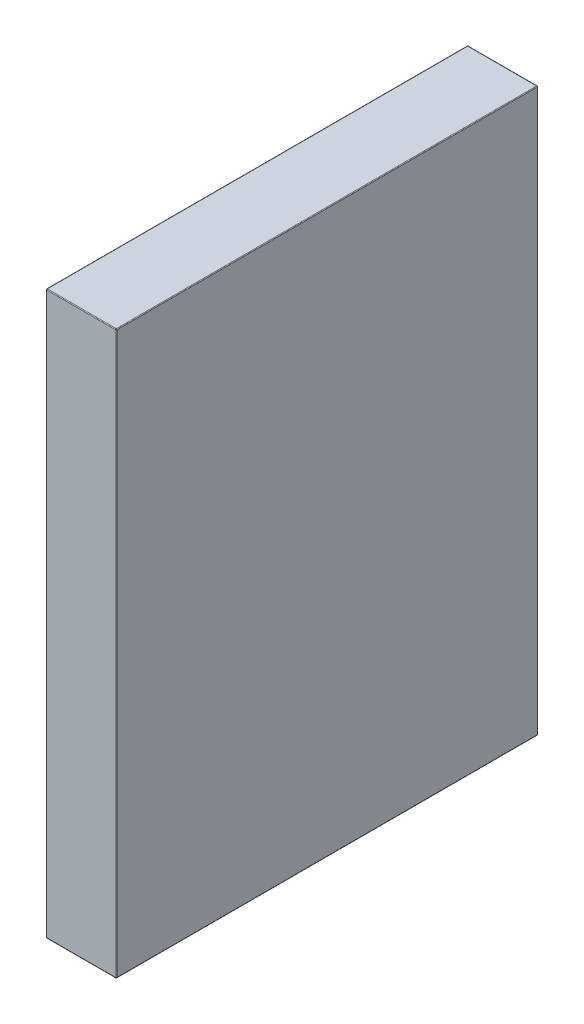
SolidWorks part; units mm, degrees
ref_plane "Front Plane" through (0, 0, 0) normal (1, 0, 0) x (0, 1, 0)
ref_plane "Top Plane" through (0, 0, 0) normal (0, 0, 1) x (0, 1, 0)
ref_plane "Right Plane" through (0, 0, 0) normal (0, 1, 0) x (-1, 0, 0)
sketch "Sketch1" plane through (0, 0, 0) normal (0, 0, 1) x (0, 1, 0)
  line L1 (-40, -5) -> (40, -5)
  line L2 (-40, -5) -> (-40, 5)
  line L3 (-40, 5) -> (40, 5)
  line L4 (40, -5) -> (40, 5)
  line L5 (-40, -5) -> (40, 5) construction
  line L6 (-40, 5) -> (40, -5) construction
  point P0 (0, 0)
  dimension "D1" = 80
  dimension "D2" = 10
extrude "Boss-Extrude1" add sketch "Sketch1" along normal blind 60
fillet "Fillet1" radius 0.1 12 edges at (-5, 40, 30) (-5, -40, 30) (5, -40, 30) (5, 40, 30) (5, 0, 60) (0, -40, 60) (-5, 0, 60) (0, 40, 60) (5, 0, 0) (0, -40, 0) (-5, 0, 0) (0, 40, 0)
